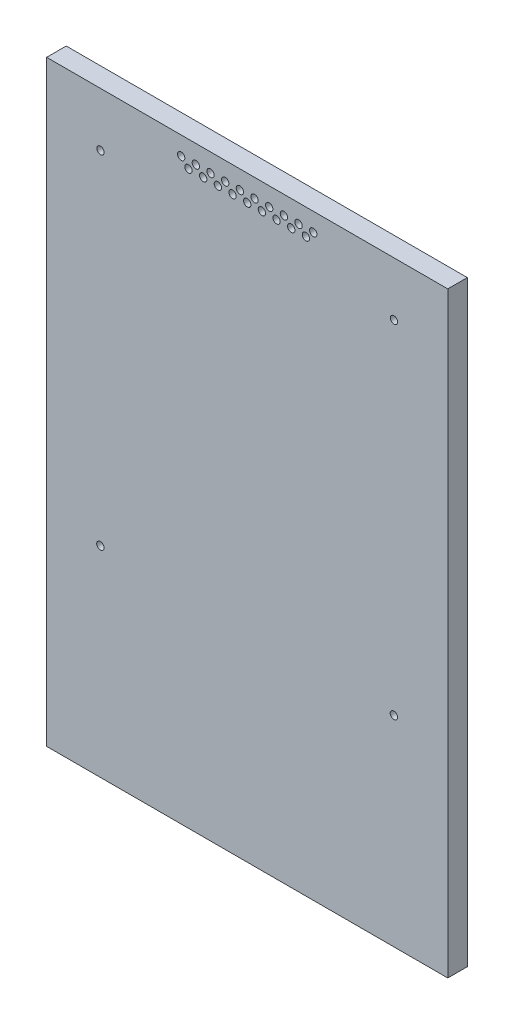
SolidWorks part; units mm, degrees
ref_plane "Front Plane" through (0, 0, 0) normal (0, 0, 1) x (1, 0, 0)
ref_plane "Top Plane" through (0, 0, 0) normal (0, 1, 0) x (1, 0, 0)
ref_plane "Right Plane" through (0, 0, 0) normal (1, 0, 0) x (0, 0, -1)
sketch "Sketch1" plane through (0, 0, 0) normal (0, 0, 1) x (1, 0, 0)
  line L1 (-41, 61) -> (41, 61)
  line L2 (-41, 61) -> (-41, -61)
  line L3 (-41, -61) -> (41, -61)
  line L4 (41, 61) -> (41, -61)
  point P4 (0, -61)
  point P7 (-41, 0)
  dimension "D1" = 82
  dimension "D2" = 122
extrude "Boss-Extrude1" add sketch "Sketch1" against normal blind 4
sketch "Sketch2" plane through (0, 0, -4) normal (0, 0, -1) x (-1, 0, 0)
  line L0 (-41, 61) -> (41, 61) construction
  line L1 (-38, 58) -> (38, 58)
  line L2 (-38, 58) -> (-38, -58)
  line L3 (-38, -58) -> (38, -58)
  line L4 (38, 58) -> (38, -58)
  line L5 (41, -61) -> (-41, -61) construction
  line L6 (-41, -61) -> (-41, 61) construction
  line L7 (41, 61) -> (41, -61) construction
  point P6 (0, -58)
  dimension "D1" = 3
  dimension "D2" = 3
  dimension "D3" = 3
  dimension "D4" = 3
extrude "Cut-Extrude1" cut sketch "Sketch2" against normal offset from surface (0.0001 mm away) 3.9999 up to face at (0, 0, 0)
sketch "Sketch6" plane through (0, 0, -4) normal (0, 0, -1) x (-1, 0, 0)
  line L0 (-38, 58) -> (-38, -58) construction
  line L1 (-39, 59) -> (39, 59)
  line L2 (-39, 59) -> (-39, -59)
  line L3 (-39, -59) -> (39, -59)
  line L4 (39, 59) -> (39, -59)
  line L5 (38, 58) -> (-38, 58) construction
  line L6 (38, -58) -> (38, 58) construction
  line L8 (-38, -58) -> (38, -58) construction
  line L9 (-38, 58) -> (38, 58)
  line L10 (-38, 58) -> (-38, -58)
  line L11 (-38, -58) -> (38, -58)
  line L12 (38, 58) -> (38, -58)
  dimension "D1" = 1
  dimension "D2" = 1
  dimension "D3" = 1
  dimension "D4" = 1
extrude "Boss-Extrude4" add sketch "Sketch6" along normal blind 1
sketch "Sketch3" plane through (0, 0, -3.9999) normal (0, 0, -1) x (-1, 0, 0)
  line L1 (38, 58) -> (-38, 58) construction
  line L2 (-38, 58) -> (-38, -58) construction
  circle A0 centre (30, 50) radius 2
  circle A1 centre (-30, 50) radius 2
  circle A2 centre (30, -20) radius 2
  circle A3 centre (-30, -20) radius 2
  dimension "D1" = 8
  dimension "D3" = 2
  dimension "D4" = 4
  dimension "D2" = 8
  dimension "D5" = 2
extrude "Boss-Extrude2" add sketch "Sketch3" along normal blind 1
sketch "Sketch5" plane through (0, 0, -4.9999) normal (0, 0, -1) x (-1, 0, 0)
  circle A0 centre (-30, 50) radius 0.75
  circle A1 centre (30, 50.0168) radius 0.75
  circle A2 centre (30.0196, -19.9832) radius 0.75
  circle A3 centre (-29.9804, -20) radius 0.75
  circle A4 centre (-30, 50) radius 2 construction
  dimension "D1" = 1.5
  dimension "D2" = 2
  dimension "D3" = 2
extrude "Cut-Extrude2" cut sketch "Sketch5" against normal through all
sketch "Sketch7" plane through (0, 0, -3.9999) normal (0, 0, -1) x (-1, 0, 0)
  line L0 (38, 58) -> (-38, 58) construction
  line L2 (38, -58) -> (38, 58) construction
  circle A0 centre (13.5, 57.25) radius 0.75
  circle A1 centre (10.5, 57.25) radius 0.75
  circle A2 centre (7.5, 57.25) radius 0.75
  circle A3 centre (4.5, 57.25) radius 0.75
  circle A4 centre (1.5, 57.25) radius 0.75
  circle A5 centre (-1.5, 57.25) radius 0.75
  circle A6 centre (-4.5, 57.25) radius 0.75
  circle A7 centre (-7.5, 57.25) radius 0.75
  circle A8 centre (-10.5, 57.25) radius 0.75
  circle A9 centre (-13.5, 57.25) radius 0.75
  circle A10 centre (12, 55.75) radius 0.75
  circle A11 centre (9, 55.75) radius 0.75
  circle A12 centre (6, 55.75) radius 0.75
  circle A13 centre (3, 55.75) radius 0.75
  circle A14 centre (0, 55.75) radius 0.75
  circle A15 centre (-3, 55.75) radius 0.75
  circle A16 centre (-6, 55.75) radius 0.75
  circle A17 centre (-9, 55.75) radius 0.75
  circle A18 centre (-12, 55.75) radius 0.75
  dimension "D1" = 1.5
  dimension "D3" = 1.5
  dimension "D6" = 9
  dimension "D4" = 1.5
  dimension "D5" = 1.5
  dimension "D7" = 24.5
  dimension "D2" = 10
extrude "Cut-Extrude3" cut sketch "Sketch7" against normal through all
